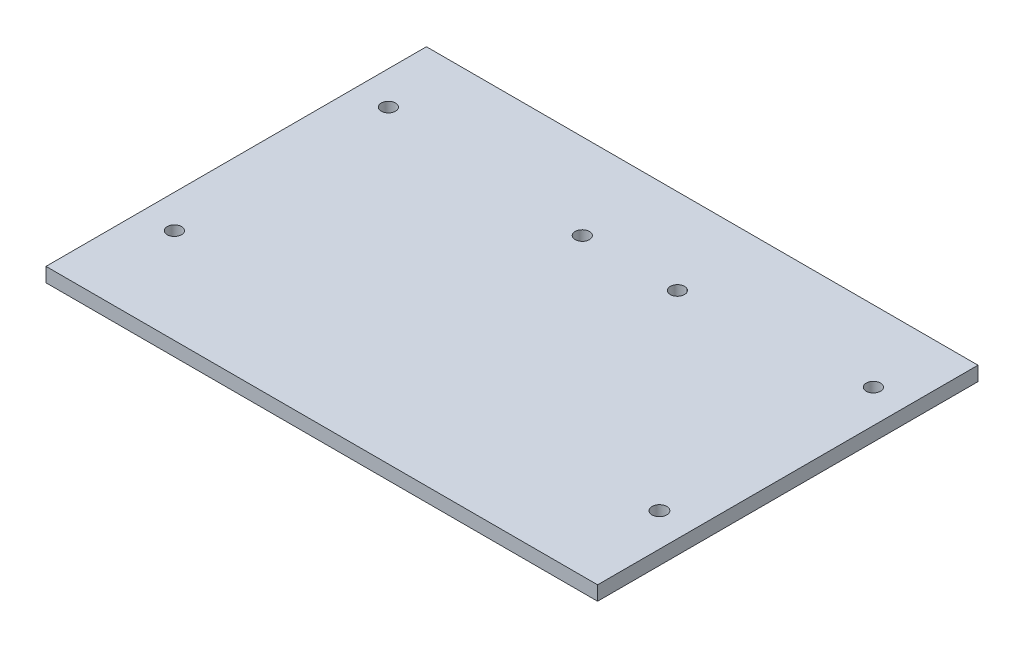
SolidWorks part; units mm, degrees
ref_plane "前视基准面" through (0, 0, 0) normal (0, 0, 1) x (1, 0, 0)
ref_plane "上视基准面" through (0, 0, 0) normal (0, 1, 0) x (1, 0, 0)
ref_plane "右视基准面" through (0, 0, 0) normal (1, 0, 0) x (0, 0, -1)
other "Configuration Table"
sketch "草图1" plane through (0, 0, 0) normal (0, 1, 0) x (1, 0, 0)
  line L1 (58, -40) -> (-58, -40)
  line L2 (58, -40) -> (58, 40)
  line L3 (58, 40) -> (-58, 40)
  line L4 (-58, -40) -> (-58, 40)
  line L5 (58, -40) -> (-58, 40) construction
  line L6 (58, 40) -> (-58, -40) construction
  point P0 (0, 0)
  dimension "D1" = 116
  dimension "D2" = 80
extrude "凸台-拉伸1" add sketch "草图1" along normal blind 3
sketch "草图2" plane through (0, 0, 0) normal (0, -1, 0) x (1, 0, 0)
  line L0 (-58, 40) -> (58, 40) construction
  line L1 (-58, -40) -> (-58, 40) construction
  line L2 (58, 40) -> (58, -40) construction
  line L3 (58, -40) -> (-58, -40) construction
  circle A0 centre (-51, 20) radius 1.5
  circle A1 centre (51, 20) radius 1.55
  circle A2 centre (51, -25) radius 1.5
  circle A3 centre (-51, -25) radius 1.5
  dimension "D1" = 20
  dimension "D2" = 7
  dimension "D3" = 7
  dimension "D4" = 20
  dimension "D5" = 15
  dimension "D6" = 7
  dimension "D7" = 7
  dimension "D8" = 15
extrude "切除-拉伸1" cut sketch "草图2" against normal blind 10
sketch "草图3" plane through (0, 3, 0) normal (0, 1, 0) x (1, 0, 0)
  circle A0 centre (-7.216, 22) radius 1.5
  circle A1 centre (12.784, 22) radius 1.5
extrude "切除-拉伸2" cut sketch "草图3" against normal through all
